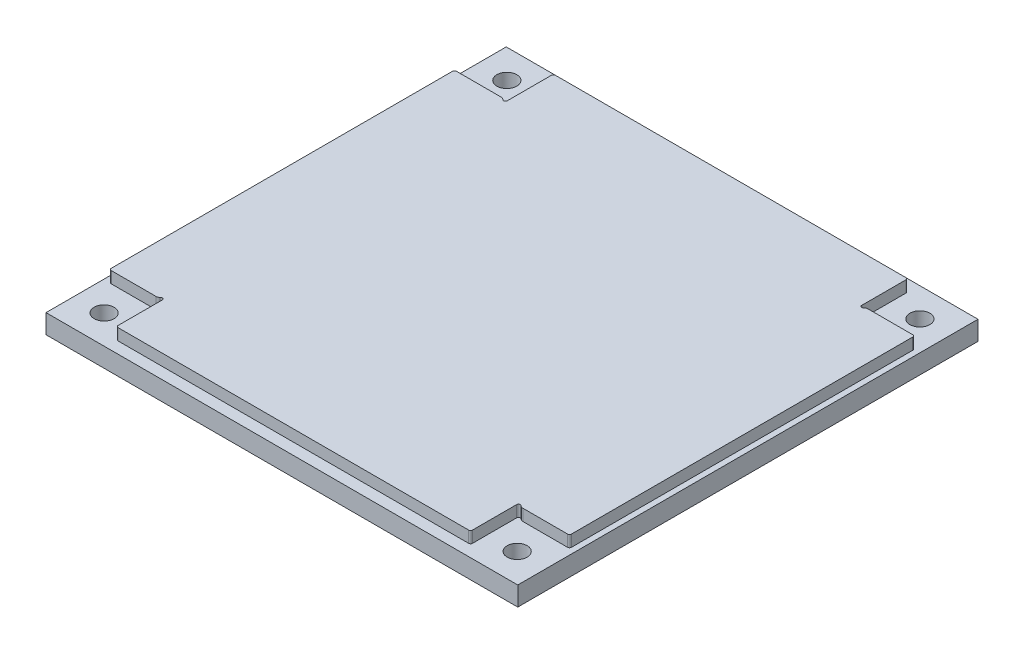
SolidWorks part; units mm, degrees
ref_plane "Front Plane" through (0, 0, 0) normal (0, 0, 1) x (1, 0, 0)
ref_plane "Top Plane" through (0, 0, 0) normal (0, 1, 0) x (1, 0, 0)
ref_plane "Right Plane" through (0, 0, 0) normal (1, 0, 0) x (0, 0, -1)
other "Configuration Table"
sketch "草图1" plane through (0, 0, 0) normal (0, 1, 0) x (1, 0, 0)
  line L1 (-60, 60) -> (60, 60)
  line L2 (-60, 60) -> (-60, -60)
  line L3 (-60, -60) -> (60, -60)
  line L4 (60, 60) -> (60, -60)
  line L5 (-60, 60) -> (60, -60) construction
  line L6 (-60, -60) -> (60, 60) construction
  point P0 (0, 0)
extrude "凸台-拉伸1" add sketch "草图1" along normal blind 3
sketch "草图3" plane through (0, 0, 0) normal (0, -1, 0) x (1, 0, 0)
  line L0 (-60, 60) -> (60, 60) construction
  line L6 (-61.5, 60) -> (61.5, 60)
  line L7 (-61.5, 60) -> (-61.5, -60)
  line L8 (-61.5, -60) -> (61.5, -60)
  line L9 (61.5, 60) -> (61.5, -60)
  line L10 (-61.5, 60) -> (61.5, -60) construction
  line L11 (-61.5, -60) -> (61.5, 60) construction
  line L12 (60, 60) -> (60, -60) construction
  point P0 (0, 0)
  dimension "D1" = 0
  dimension "D2" = 1.5
extrude "凸台-拉伸2" add sketch "草图3" along normal blind 5
sketch "草图5" plane through (0, 3, 0) normal (0, 1, 0) x (1, 0, 0)
  line L0 (-61.5, 60) -> (-46.2, 60)
  line L1 (60, 60) -> (-60, 60) construction
  line L2 (-46.2, 60) -> (-46.2, 45)
  line L3 (-46.2, 45) -> (-61.5, 45)
  line L4 (-61.5, -60) -> (-61.5, 60) construction
  line L5 (-61.5, 45) -> (-61.5, 60)
  line L6 (46.2, 60) -> (46.2, 45)
  line L7 (46.2, 45) -> (61.5, 45)
  line L8 (61.5, 60) -> (61.5, -60) construction
  line L9 (61.5, 45) -> (61.5, 60)
  line L10 (61.5, 60) -> (46.2, 60)
  line L19 (-61.5, -60) -> (-46.2, -60)
  line L20 (-46.2, -60) -> (-46.2, -45)
  line L21 (-46.2, -45) -> (-61.5, -45)
  line L22 (-61.5, -45) -> (-61.5, -60)
  line L23 (61.5, -60) -> (46.2, -60)
  line L24 (-60, -60) -> (60, -60) construction
  line L25 (46.2, -60) -> (46.2, -45)
  line L26 (46.2, -45) -> (61.5, -45)
  line L27 (61.5, -45) -> (61.5, -60)
extrude "切除-拉伸2" cut sketch "草图5" against normal blind 3
sketch "草图6" plane through (0, 3, 0) normal (0, 1, 0) x (1, 0, 0)
  line L0 (46.2, 52.5) -> (61.5, 52.5) construction
  line L1 (-61.5, -60) -> (-61.5, 60) construction
  line L3 (61.5, 60) -> (61.5, -60) construction
  line L4 (46.2, 60) -> (46.2, 45) construction
  line L5 (-46.2, 60) -> (-46.2, 45) construction
  line L6 (-46.2, -45) -> (-46.2, -60) construction
  line L8 (46.2, -45) -> (46.2, -60) construction
  line L9 (-46.2, -52.5) -> (-61.5, -52.5) construction
  line L10 (-46.2, 52.5) -> (-61.5, 52.5) construction
  line L11 (46.2, -52.5) -> (61.5, -52.5) construction
  circle A0 centre (-53.85, 52.5) radius 2.6
  circle A3 centre (53.85, 52.5) radius 2.6
  circle A4 centre (-53.85, -52.5) radius 2.6
  circle A5 centre (53.85, -52.5) radius 2.6
extrude "切除-拉伸3" cut sketch "草图6" against normal through all
sketch "草图7" plane through (0, -5, 0) normal (0, -1, 0) x (1, 0, 0)
  circle A0 centre (-53.85, 52.5) radius 5.5
  circle A1 centre (-53.85, -52.5) radius 5.5
  circle A3 centre (53.85, 52.5) radius 5.5
  circle A4 centre (53.85, -52.5) radius 5.5
extrude "切除-拉伸4" cut sketch "草图7" against normal blind 1
sketch "草图8" plane through (0, 3, 0) normal (0, 1, 0) x (1, 0, 0)
  line L0 (-46.2, 60) -> (-46.2, 57)
  line L1 (-46.2, 45) -> (-46.2, 60) construction
  line L2 (-46.2, 57) -> (46.2, 57)
  line L3 (46.2, 60) -> (46.2, 45) construction
  line L4 (46.2, 57) -> (46.2, 60)
  line L5 (46.2, 60) -> (-46.2, 60)
  line L6 (-46.2, -60) -> (-46.2, -57)
  line L7 (-46.2, -60) -> (-46.2, -45) construction
  line L8 (-46.2, -57) -> (46.2, -57)
  line L9 (46.2, -45) -> (46.2, -60) construction
  line L10 (46.2, -57) -> (46.2, -60)
  line L11 (46.2, -60) -> (-46.2, -60)
  line L12 (-46.2, -60) -> (-46.2, -45) construction
extrude "切除-拉伸5" cut sketch "草图8" against normal blind 3
sketch "草图9" plane through (0, 3, 0) normal (0, 1, 0) x (1, 0, 0)
  line L0 (-46.2, 45) -> (-46.7, 45) construction
  line L1 (-60, 45) -> (-46.2, 45) construction
  line L2 (46.2, 45) -> (46.7, 45) construction
  line L3 (46.2, 45) -> (60, 45) construction
  line L4 (-46.2, -45) -> (-46.7, -45) construction
  line L5 (-46.2, -45) -> (-60, -45) construction
  line L6 (46.2, -45) -> (46.7, -45) construction
  line L7 (60, -45) -> (46.2, -45) construction
  circle A0 centre (-46.7, 45) radius 0.5
  circle A1 centre (46.7, 45) radius 0.5
  circle A2 centre (-46.7, -45) radius 0.5
  circle A3 centre (46.7, -45) radius 0.5
extrude "切除-拉伸6" cut sketch "草图9" against normal up to surface (3 mm away) up to face at (0, 0, 0)
fillet "圆角1" radius 1 4 edges at (47.2, 1.5, 45) (-47.2, 1.5, 45) (-47.2, 1.5, -45) (47.2, 1.5, -45)
fillet "圆角2" radius 0.5 8 edges at (60, 1.5, -45) (46.2, 1.5, -57) (-46.2, 1.5, -57) (-60, 1.5, -45) (-60, 1.5, 45) (-46.2, 1.5, 57) (46.2, 1.5, 57) (60, 1.5, 45)
